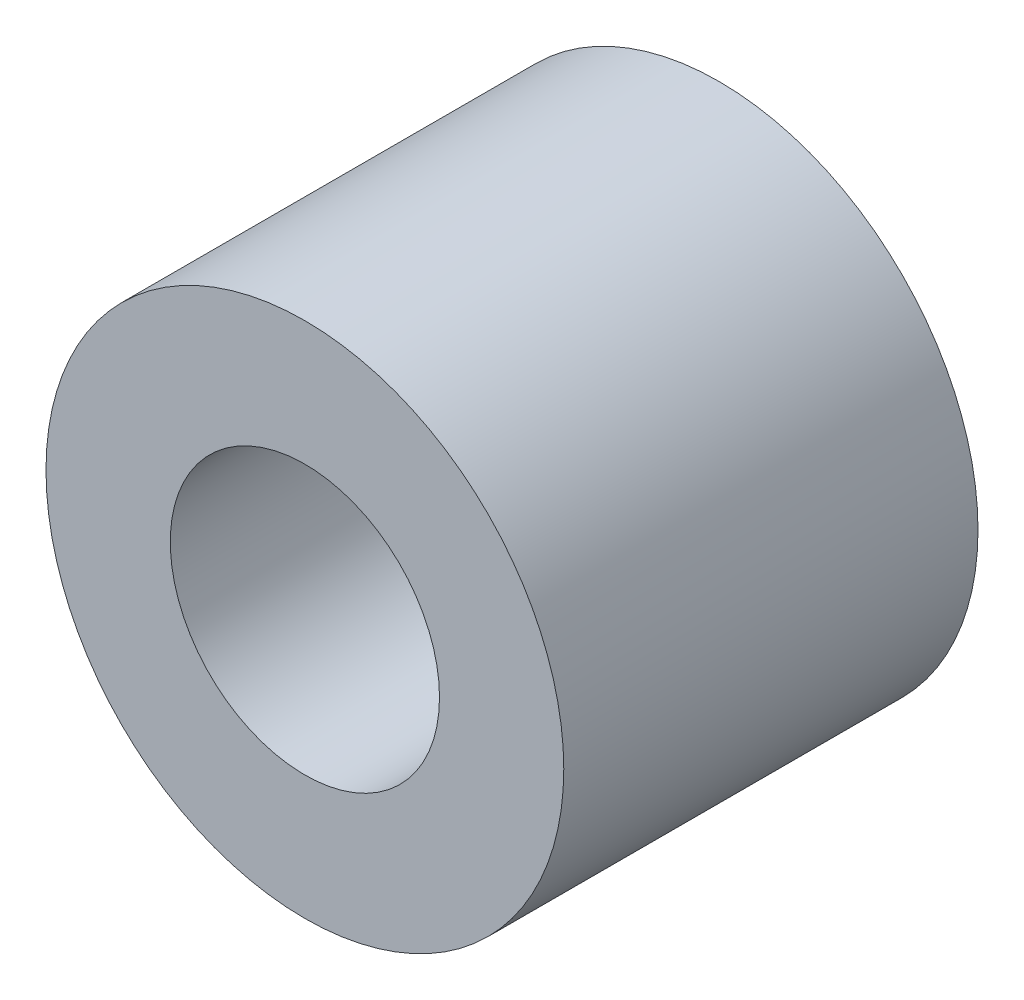
SolidWorks part; units mm, degrees
ref_plane "Front Plane" through (0, 0, 0) normal (0, 0, 1) x (1, 0, 0)
ref_plane "Top Plane" through (0, 0, 0) normal (0, 1, 0) x (1, 0, 0)
ref_plane "Right Plane" through (0, 0, 0) normal (1, 0, 0) x (0, 0, -1)
sketch "Sketch1" plane through (0, 0, 0) normal (0, 0, 1) x (1, 0, 0)
  circle A0 centre (0, 0) radius 1.651
  circle A1 centre (0, 0) radius 3.175
  dimension "D1" = 3.302
  dimension "D2" = 6.35
extrude "Boss-Extrude1" add sketch "Sketch1" along normal blind 5.08
